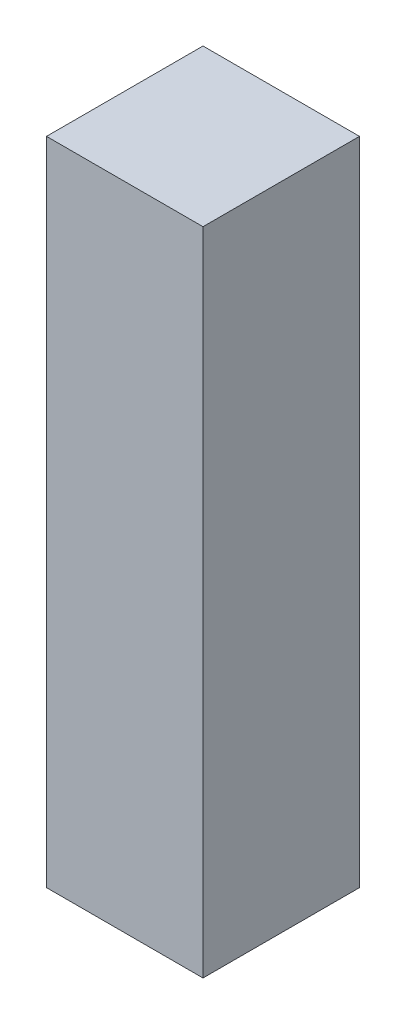
SolidWorks part; units mm, degrees
material "ABS"
ref_plane "Front Plane" through (0, 0, 0) normal (0, 0, 1) x (1, 0, 0)
ref_plane "Top Plane" through (0, 0, 0) normal (0, 1, 0) x (1, 0, 0)
ref_plane "Right Plane" through (0, 0, 0) normal (1, 0, 0) x (0, 0, -1)
sketch "Sketch1" plane through (0, 0, 0) normal (0, 1, 0) x (1, 0, 0)
  line L1 (0, 0) -> (38, 0)
  line L2 (0, 0) -> (0, 38)
  line L3 (0, 38) -> (38, 38)
  line L4 (38, 0) -> (38, 38)
  dimension "D1" = 38
  dimension "D2" = 38
extrude "Boss-Extrude1" add sketch "Sketch1" along normal blind 158
